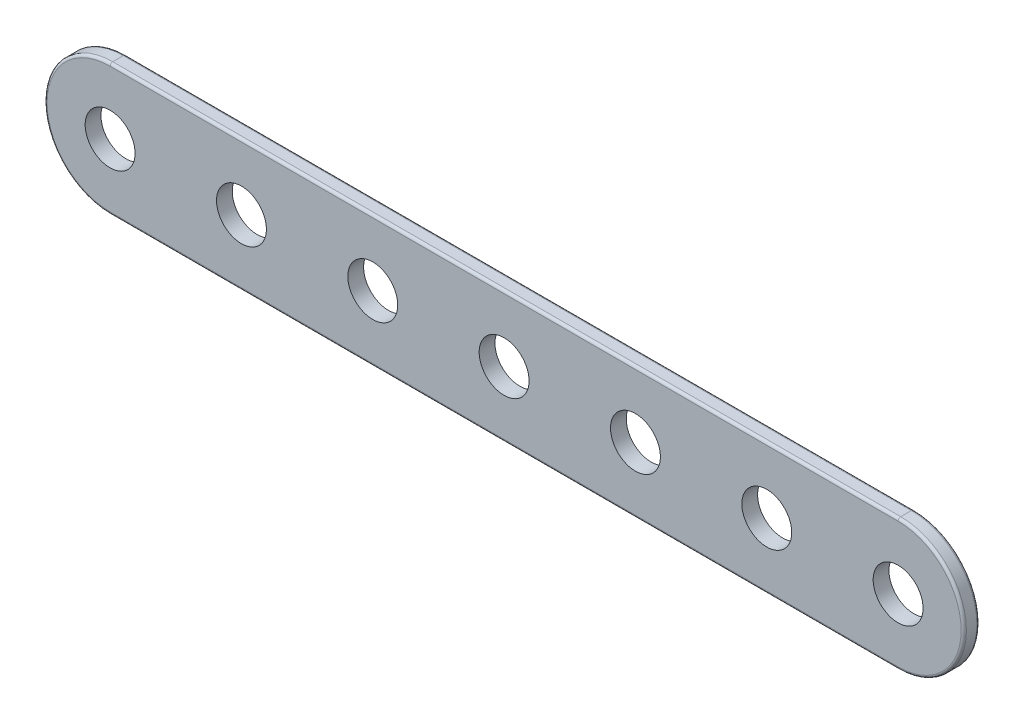
SolidWorks part; units mm, degrees
material "AISI 304"
ref_plane "Front Plane" through (0, 0, 0) normal (0, 0, 1) x (1, 0, 0)
ref_plane "Top Plane" through (0, 0, 0) normal (0, 1, 0) x (1, 0, 0)
ref_plane "Right Plane" through (0, 0, 0) normal (1, 0, 0) x (0, 0, -1)
sketch "Sketch1" plane through (0, 0, 0) normal (0, 0, 1) x (1, 0, 0)
  line L1 (-38.1, -6.35) -> (38.1, -6.35)
  line L3 (-38.1, 6.35) -> (38.1, 6.35)
  line L5 (-38.1, -6.35) -> (38.1, 6.35) construction
  line L6 (-38.1, 6.35) -> (38.1, -6.35) construction
  arc A0 (38.1, 6.35) -> (38.1, -6.35) centre (38.1, 0) cw
  arc A1 (-38.1, 6.35) -> (-38.1, -6.35) centre (-38.1, 0) ccw
  point P0 (0, 0)
  dimension "D2" = 6.35
  dimension "D1" = 76.2
extrude "Extrude1" add sketch "Sketch1" along normal blind 1.524
sketch "Sketch2" plane through (0, 0, 1.524) normal (0, 0, 1) x (1, 0, 0)
  circle A0 centre (-38.1, 0) radius 2.413
  dimension "D1" = 4.826
extrude "Extrude2" cut sketch "Sketch2" against normal through all
pattern_linear "LPattern1" count 7 spacing 12.7 along (1, 0, 0) of "Extrude2"
fillet "Fillet1" radius 0.254 8 edges at (44.45, 0, 0) (0, -6.35, 0) (-44.45, 0, 0) (44.45, 0, 1.524) (0, -6.35, 1.524) (-44.45, 0, 1.524) (0, 6.35, 0) (0, 6.35, 1.524)
